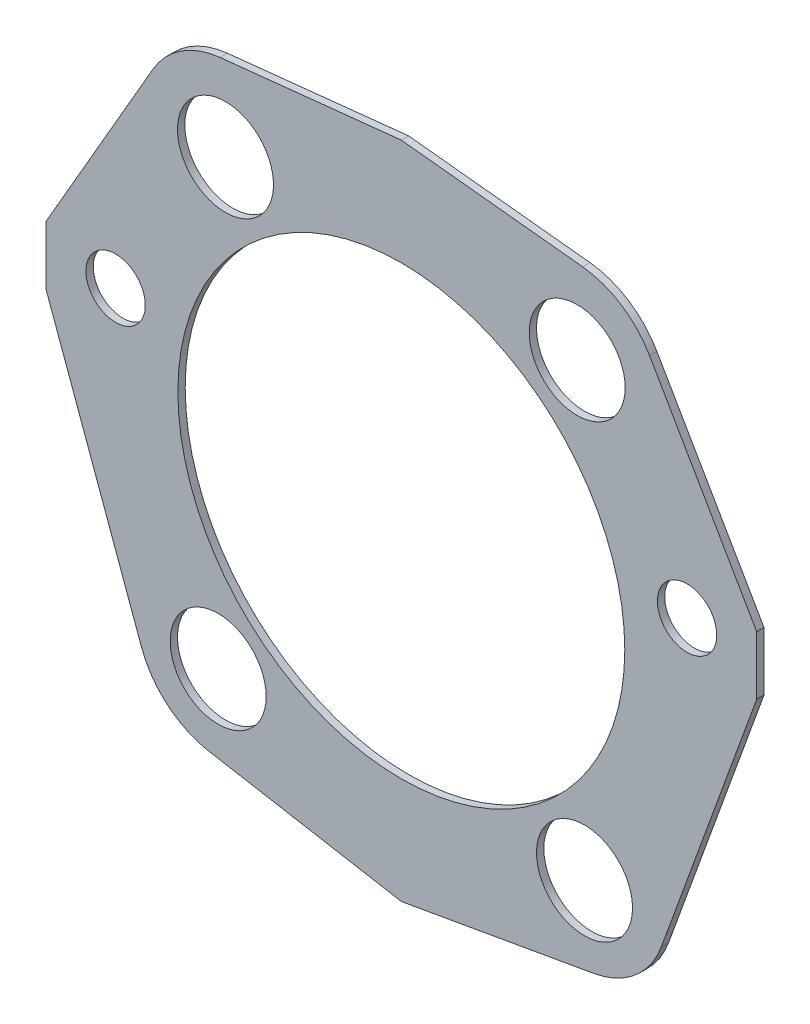
SolidWorks part; units mm, degrees
material "GASKET PAPER"
ref_plane "Front Plane" through (0, 0, 0) normal (0, 0, 1) x (1, 0, 0)
ref_plane "Top Plane" through (0, 0, 0) normal (0, 1, 0) x (1, 0, 0)
ref_plane "Right Plane" through (0, 0, 0) normal (1, 0, 0) x (0, 0, -1)
sketch "Sketch1" plane through (0, 0, 0) normal (0, 0, 1) x (1, 0, 0)
  line L0 (57.089, 0) -> (0, 0) construction
  line L1 (0, 0) -> (0, 56.1599) construction
  line L2 (0, 45) -> (24.7425, 42.3995)
  line L3 (33.8804, 36.4652) -> (48.5, 11.1434)
  line L4 (48.5, 11.1434) -> (48.5, 3.1434)
  line L5 (48.5, 3.1434) -> (35.4712, -32.6529)
  line L6 (26.2787, -40.3664) -> (0, -45)
  line L7 (-26.2787, -40.3664) -> (0, -45)
  line L8 (-48.5, 3.1434) -> (-35.4712, -32.6529)
  line L9 (-48.5, 11.1434) -> (-48.5, 3.1434)
  line L10 (-33.8804, 36.4652) -> (-48.5, 11.1434)
  line L11 (0, 45) -> (-24.7425, 42.3995)
  arc A0 (35.4712, -32.6529) -> (26.2787, -40.3664) centre (24.1949, -28.5487) cw
  arc A1 (24.7425, 42.3995) -> (33.8804, 36.4652) centre (23.4881, 30.4652) cw
  circle A2 centre (0, 0) radius 30.5
  arc A3 (-35.4712, -32.6529) -> (-26.2787, -40.3664) centre (-24.1949, -28.5487) ccw
  arc A4 (-24.7425, 42.3995) -> (-33.8804, 36.4652) centre (-23.4881, 30.4652) ccw
  circle A5 centre (24, 31) radius 6.55
  circle A6 centre (-24, 31) radius 6.55
  circle A7 centre (-25, -30) radius 6.55
  circle A8 centre (25, -30) radius 6.55
  circle A9 centre (39, 8) radius 4.05
  circle A10 centre (-39, 8) radius 4.05
  dimension "D6" = 12
  dimension "D12" = 61
  dimension "D13" = 14
  dimension "D14" = 13.1
  dimension "D19" = 8.1
  dimension "D1" = 6
  dimension "D2" = 54
  dimension "D3" = 30
  dimension "D4" = 8
  dimension "D5" = 48.5
  dimension "D7" = 45
  dimension "D8" = 90
  dimension "D9" = 10
  dimension "D10" = 60
  dimension "D11" = 20
  dimension "D15" = 31
  dimension "D16" = 24
  dimension "D17" = 30
  dimension "D18" = 25
  dimension "D20" = 39
  dimension "D21" = 8
extrude "Boss-Extrude1" add sketch "Sketch1" against normal blind 1
